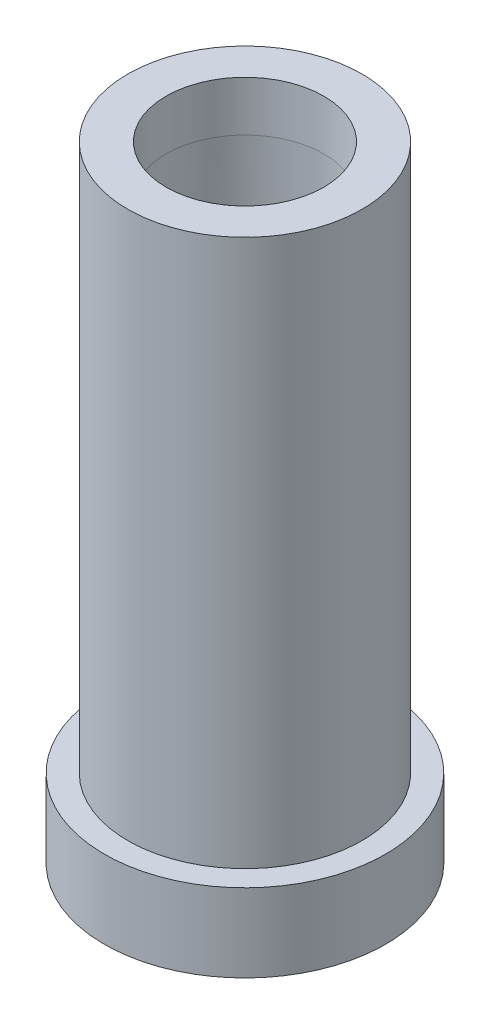
SolidWorks part; units mm, degrees
material "K110"
ref_plane "Front Plane" through (0, 0, 0) normal (0, 0, 1) x (1, 0, 0)
ref_plane "Top Plane" through (0, 0, 0) normal (0, 1, 0) x (1, 0, 0)
ref_plane "Right Plane" through (0, 0, 0) normal (1, 0, 0) x (0, 0, -1)
sketch "Sketch1" plane through (0, 0, 0) normal (0, 0, 1) x (1, 0, 0)
  line L0 (0, 0) -> (9, 0)
  line L1 (9, 0) -> (9, 5)
  line L2 (9, 5) -> (7.5, 5)
  line L3 (7.5, 5) -> (7.5, 40)
  line L4 (7.5, 40) -> (0, 40)
  line L5 (0, 40) -> (0, 0)
  line L6 (0, 45) -> (0, -5) construction
  line L7 (11, 0) -> (-11, 0) construction
  dimension "D1" = 5
  dimension "D2" = 5
  dimension "D3" = 15
  dimension "D4" = 18
  dimension "D5" = 5
  dimension "D6" = 40
revolve "Revolve1" add sketch "Sketch1" angle 360 about L6
sketch "Sketch2" plane through (0, 40, 0) normal (0, 1, 0) x (1, 0, 0)
  circle A0 centre (0, 0) radius 5.05
  dimension "D1" = 10.1
extrude "Cut-Extrude1" cut sketch "Sketch2" against normal up to next
sketch "Sketch4" plane through (0, 40, 0) normal (0, 1, 0) x (1, 0, 0)
  circle A0 centre (0, 0) radius 5.05 construction
  circle A1 centre (0, 0) radius 5.05
sketch "Sketch3" plane through (0, 0, 0) normal (0, 0, 1) x (1, 0, 0)
  line L0 (5.05, 36.8) -> (6.0136, 0)
  line L1 (5.05, 0) -> (5.05, 40) construction
  line L2 (11, 0) -> (-11, 0) construction
  line L3 (6.0136, 0) -> (5.05, 0)
  line L4 (5.05, 0) -> (5.05, 36.8)
  line L5 (7.5, 40) -> (-7.5, 40) construction
  dimension "D1" = 3.2
  dimension "D2" = 1.5
sweep "Cut-Sweep1" cut profiles "Sketch3" path "Sketch4"
